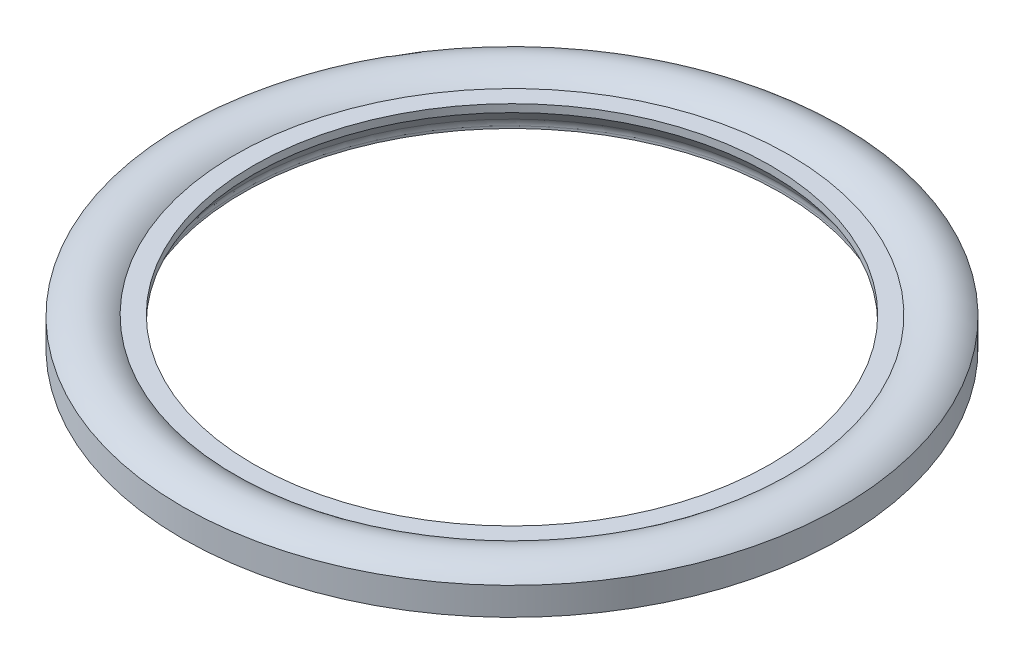
SolidWorks part; units mm, degrees
ref_plane "Plano frontal" through (0, 0, 0) normal (0, 0, 1) x (1, 0, 0)
ref_plane "Plano superior" through (0, 0, 0) normal (0, 1, 0) x (1, 0, 0)
ref_plane "Plano direito" through (0, 0, 0) normal (1, 0, 0) x (0, 0, -1)
sketch "Esboço1" plane through (0, 0, 0) normal (0, 0, 1) x (1, 0, 0)
  line L0 (0, -31.9188) -> (0, 32.636) construction
  line L1 (41.75, 0) -> (51.1, 0)
  line L2 (51.1, 0) -> (51.1, 4.3)
  line L3 (42.9705, 4.5) -> (40.1, 4.5)
  line L4 (40.1, 4.5) -> (40.1, 3.3)
  line L5 (40.1, 3.3) -> (41.75, 1)
  line L6 (41.75, 1) -> (41.75, 0)
  arc A0 (51.1, 4.3) -> (42.9705, 4.5) centre (46.9267, -0.0109) ccw
  dimension "D4" = 1
  dimension "D8" = 6
  dimension "D1" = 41.75
  dimension "D2" = 51.1
  dimension "D3" = 40.1
  dimension "D5" = 3.3
  dimension "D6" = 4.5
  dimension "D7" = 4.3
revolve "Revolução1" add sketch "Esboço1" angle 360 about L0
fillet "Filete1" radius 2 1 edges at (0, 1, -41.75)
